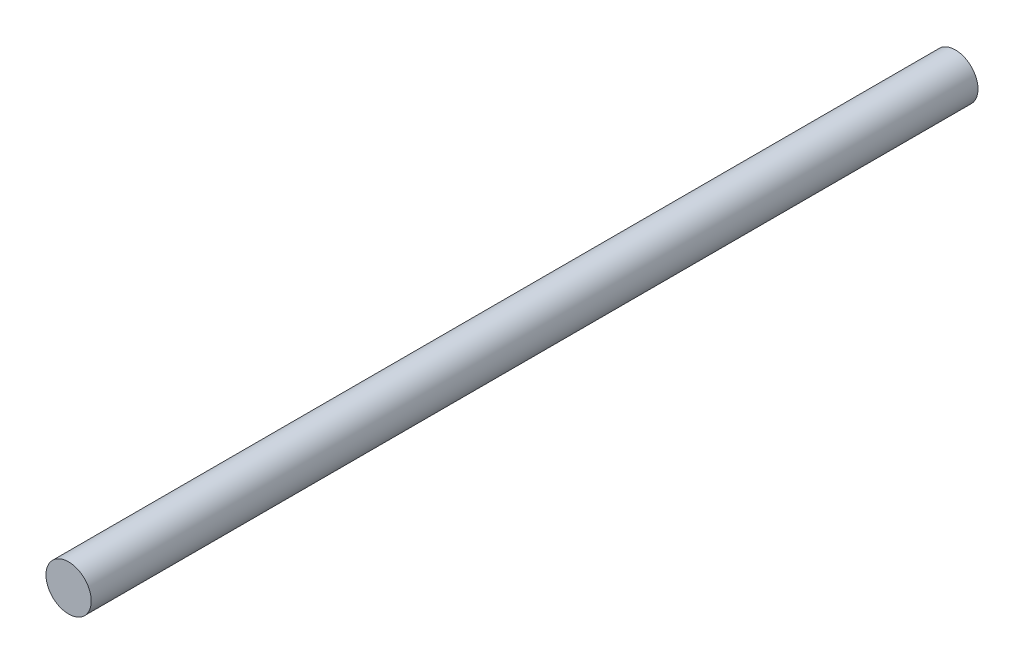
SolidWorks part; units mm, degrees
ref_plane "Front Plane" through (0, 0, 0) normal (0, 0, 1) x (1, 0, 0)
ref_plane "Top Plane" through (0, 0, 0) normal (0, 1, 0) x (1, 0, 0)
ref_plane "Right Plane" through (0, 0, 0) normal (1, 0, 0) x (0, 0, -1)
sketch "Sketch1" plane through (0, 0, 0) normal (0, 0, 1) x (1, 0, 0)
  circle A0 centre (0, 0) radius 1.94
  dimension "D1" = 3.88
extrude "Boss-Extrude1" add sketch "Sketch1" along normal blind 76
